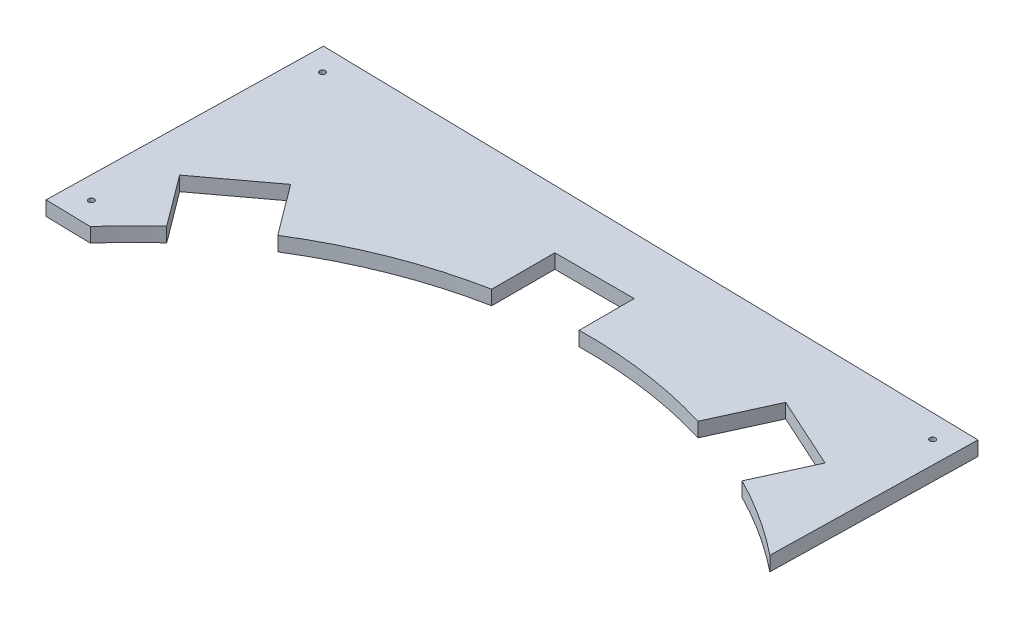
SolidWorks part; units mm, degrees
material "Balsa"
ref_plane "Front Plane" through (0, 0, 0) normal (0, 0, 1) x (1, 0, 0)
ref_plane "Top Plane" through (0, 0, 0) normal (0, 1, 0) x (1, 0, 0)
ref_plane "Right Plane" through (0, 0, 0) normal (1, 0, 0) x (0, 0, -1)
sketch "Sketch1" plane through (0, 0, 0) normal (0, 1, 0) x (1, 0, 0)
  line L0 (-12.8843, 57.5899) -> (-32.8801, 58.0016)
  line L5 (-32.8801, 58.0016) -> (-30.4097, 177.9762)
  line L6 (-30.4097, 177.9762) -> (264.5278, 171.9031)
  line L7 (264.5278, 171.9031) -> (262.6746, 81.9031)
  line L8 (99.6149, 122.2056) -> (99.6149, 150.073)
  line L9 (99.6149, 150.073) -> (134.6149, 150.073)
  line L10 (134.6149, 150.073) -> (134.6149, 125.8222)
  line L11 (195.598, 117.2478) -> (207.7139, 143.8488)
  line L12 (207.7139, 143.8488) -> (239.5656, 129.3413)
  line L13 (239.5656, 129.3413) -> (228.1093, 104.1884)
  line L14 (3.8471, 74.5464) -> (-12.8708, 96.9717)
  line L15 (-12.8708, 96.9717) -> (15.1898, 117.8906)
  line L16 (15.1898, 117.8906) -> (31.8184, 95.5852)
  arc A0 (-12.8843, 57.5899) -> (3.8471, 74.5464) centre (137.592, -74.1557) cw
  arc A1 (31.8184, 95.5852) -> (99.6149, 122.2056) centre (137.592, -74.1557) cw
  arc A2 (134.6149, 125.8222) -> (195.598, 117.2478) centre (137.592, -74.1557) cw
  arc A3 (228.1093, 104.1884) -> (262.6746, 81.9031) centre (137.592, -74.1557) cw
  circle A4 centre (-20.6177, 167.7724) radius 1.25
  circle A5 centre (254.3241, 162.1111) radius 1.25
  circle A6 centre (-22.6763, 67.7936) radius 1.25
  point P26 (0, 0)
  dimension "D5" = 200
  dimension "D11" = 2.5
  dimension "D14" = 2.5
  dimension "D17" = 2.5
  dimension "D1" = 295
  dimension "D2" = 20
  dimension "D3" = 120
  dimension "D4" = 90
  dimension "D6" = 35
  dimension "D7" = 35
  dimension "D8" = 35
  dimension "D9" = 10
  dimension "D10" = 10
  dimension "D12" = 10
  dimension "D13" = 10
  dimension "D15" = 10
  dimension "D16" = 10
extrude "Boss-Extrude1" add sketch "Sketch1" along normal blind 6.35
